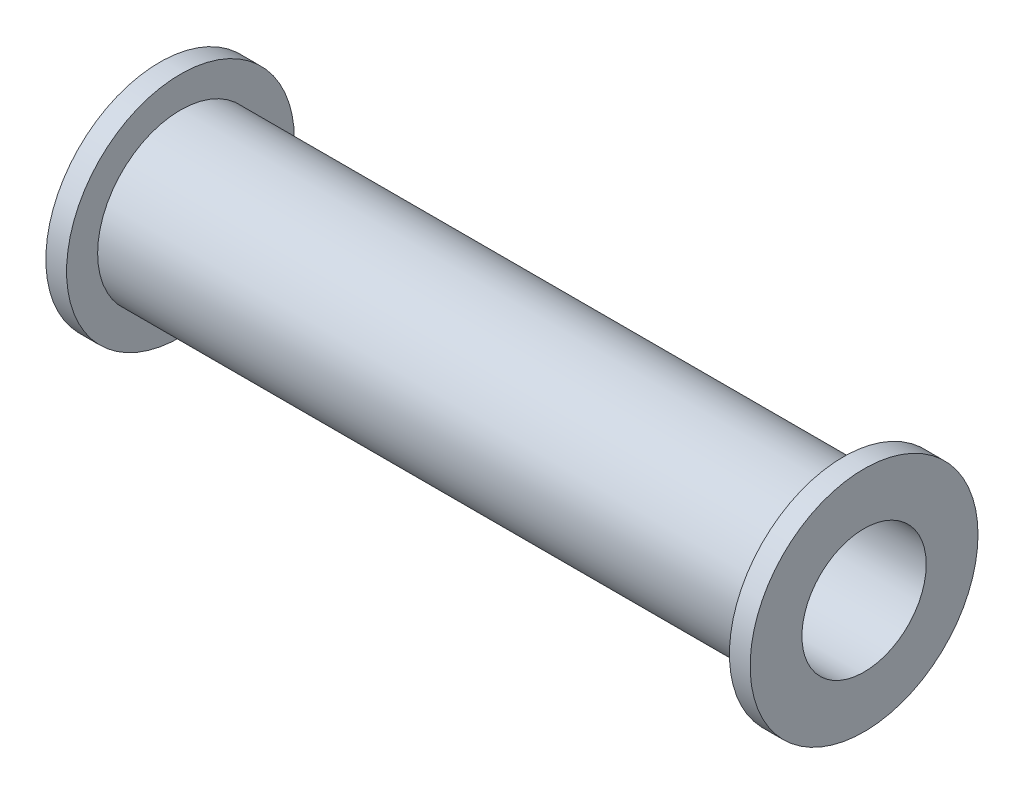
SolidWorks part; units mm, degrees
ref_plane "Front Plane" through (0, 0, 0) normal (0, 0, 1) x (1, 0, 0)
ref_plane "Top Plane" through (0, 0, 0) normal (0, 1, 0) x (1, 0, 0)
ref_plane "Right Plane" through (0, 0, 0) normal (1, 0, 0) x (0, 0, -1)
sketch "Sketch1" plane through (0, 0, 0) normal (1, 0, 0) x (0, 0, -1)
  circle A0 centre (0, 0) radius 8.7312
  dimension "D1" = 17.4625
extrude "Boss-Extrude1" add sketch "Sketch1" along normal blind 1.5875
sketch "Sketch2" plane through (1.5875, 0, 0) normal (1, 0, 0) x (0, 0, -1)
  circle A0 centre (0, 0) radius 6.35
  dimension "D1" = 12.7
extrude "Boss-Extrude2" add sketch "Sketch2" along normal blind 50.8
sketch "Sketch3" plane through (52.3875, 0, 0) normal (1, 0, 0) x (0, 0, -1)
  circle A0 centre (0, 0) radius 8.7312
  dimension "D1" = 17.4625
extrude "Boss-Extrude3" add sketch "Sketch3" along normal blind 1.5875
sketch "Sketch4" plane through (53.975, 0, 0) normal (1, 0, 0) x (0, 0, -1)
  circle A0 centre (0, 0) radius 4.7625
extrude "Cut-Extrude1" cut sketch "Sketch4" against normal through all
